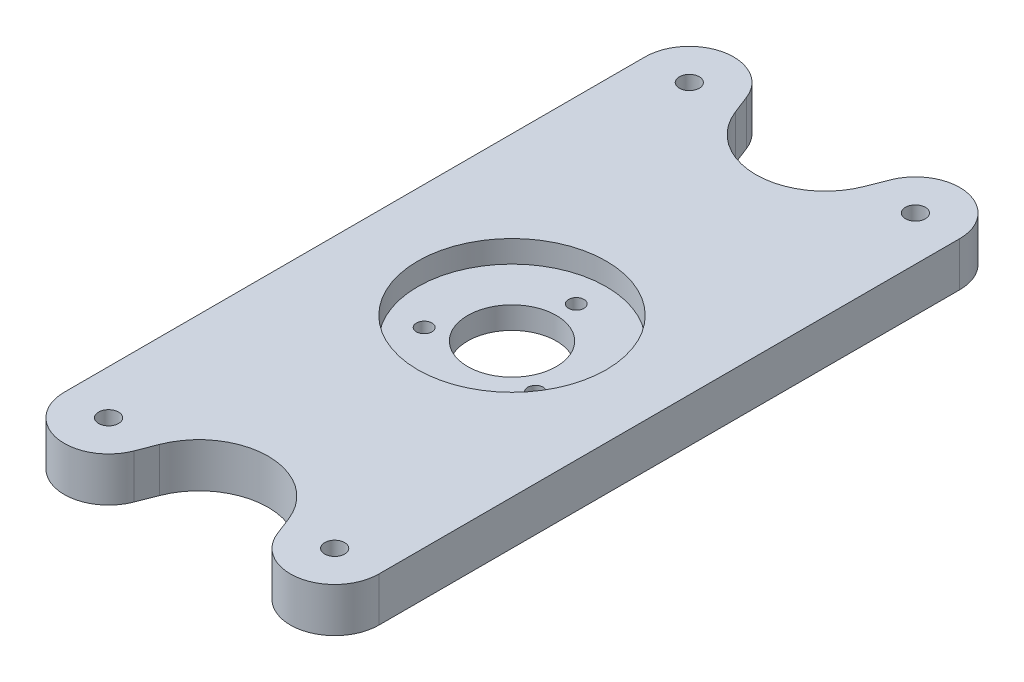
SolidWorks part; units mm, degrees
ref_plane "Front Plane" through (0, 0, 0) normal (0, 0, 1) x (1, 0, 0)
ref_plane "Top Plane" through (0, 0, 0) normal (0, 1, 0) x (1, 0, 0)
ref_plane "Right Plane" through (0, 0, 0) normal (1, 0, 0) x (0, 0, -1)
sketch "Sketch1" plane through (0, 0, 0) normal (0, 1, 0) x (1, 0, 0)
  line L0 (-25.5, 65.5) -> (25.5, -65.5) construction
  line L1 (-25.5, -65.5) -> (25.5, -65.5) construction
  line L2 (-25.5, -65.5) -> (-25.5, 65.5) construction
  line L3 (-25.5, 65.5) -> (25.5, 65.5) construction
  line L4 (25.5, -65.5) -> (25.5, 65.5) construction
  line L5 (-25.5, -65.5) -> (25.5, 65.5) construction
  line L6 (-25.5, 65.5) -> (25.5, -65.5) construction
  line L7 (-16.1813, 69.1279) -> (-14.5561, 64.9534)
  line L9 (25.5, 65.5) -> (-25.5, -65.5) construction
  line L11 (16.1813, 69.1279) -> (14.5561, 64.9534)
  line L13 (-22.5, -55) -> (22.5, -55) construction
  line L14 (-22.5, -55) -> (-22.5, 55) construction
  line L15 (-22.5, 55) -> (22.5, 55) construction
  line L16 (22.5, -55) -> (22.5, 55) construction
  line L17 (-22.5, -55) -> (22.5, 55) construction
  line L18 (-22.5, 55) -> (22.5, -55) construction
  line L19 (14.5561, -64.9534) -> (16.1813, -69.1279)
  line L22 (-14.5561, -64.9534) -> (-16.1813, -69.1279)
  line L23 (0, 0) -> (0, 65.5) construction
  line L24 (0, 0) -> (25.5, 0) construction
  line L26 (35.5, 65.5) -> (35.5, -65.5)
  line L27 (-35.5, 65.5) -> (-35.5, -65.5)
  circle A13 centre (25.5, 65.5) radius 2.25
  circle A14 centre (-25.5, 65.5) radius 2.25
  circle A17 centre (-25.5, -65.5) radius 2.25
  circle A19 centre (25.5, -65.5) radius 2.25
  arc A20 (-16.1813, 69.1279) -> (-35.5, 65.5) centre (-25.5, 65.5) ccw
  arc A23 (16.1813, -69.1279) -> (35.5, -65.5) centre (25.5, -65.5) ccw
  arc A25 (35.5, 65.5) -> (16.1813, 69.1279) centre (25.5, 65.5) ccw
  arc A26 (-35.5, -65.5) -> (-16.1813, -69.1279) centre (-25.5, -65.5) ccw
  arc A38 (-14.5561, 64.9534) -> (14.5561, 64.9534) centre (0, 70.6203) ccw
  arc A39 (-14.5561, -64.9534) -> (14.5561, -64.9534) centre (0, -70.6203) cw
  point P0 (0, 0)
  point P9 (0, 0)
  point P14 (0, 0)
  point P19 (0, 0)
  dimension "D1" = 51
  dimension "D2" = 131
  dimension "D5" = 10
  dimension "D3" = 4.5
  dimension "D6" = 45
  dimension "D7" = 110
extrude "凸台-拉伸1" add sketch "Sketch1" along normal blind 10
sketch "草图1" plane through (0, 10, 0) normal (0, 1, 0) x (1, 0, 0)
  circle A0 centre (0, 0) radius 21.25
  dimension "D1" = 42.5
extrude "切除-拉伸1" cut sketch "草图1" against normal blind 5 contours A0
sketch "草图2" plane through (0, 5, 0) normal (0, 1, 0) x (1, 0, 0)
  circle A0 centre (0, 14.5) radius 1.75
  circle A1 centre (12.5574, -7.25) radius 1.75
  circle A2 centre (-12.5574, -7.25) radius 1.75
  circle A3 centre (0, 0) radius 10
  point P9 (0, 0)
  dimension "D2" = 3.5
  dimension "D3" = 20
  dimension "D1" = 14.5
extrude "切除-拉伸2" cut sketch "草图2" against normal blind 5
